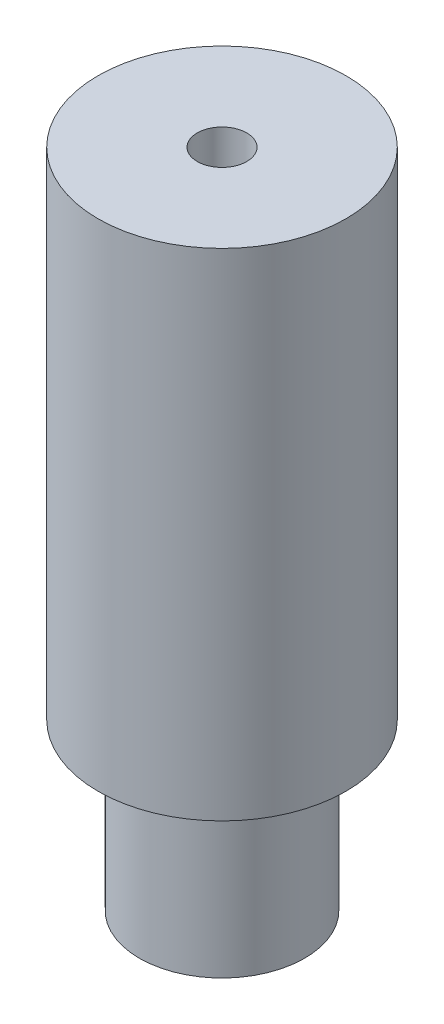
SolidWorks part; units mm, degrees
ref_plane "Front Plane" through (0, 0, 0) normal (0, 0, 1) x (1, 0, 0)
ref_plane "Top Plane" through (0, 0, 0) normal (0, 1, 0) x (1, 0, 0)
ref_plane "Right Plane" through (0, 0, 0) normal (1, 0, 0) x (0, 0, -1)
sketch "Sketch1" plane through (0, 0, 0) normal (0, 1, 0) x (1, 0, 0)
  circle A0 centre (0, 0) radius 5
  dimension "D1" = 10
extrude "Boss-Extrude1" add sketch "Sketch1" along normal blind 10
sketch "Sketch2" plane through (0, 10, 0) normal (0, 1, 0) x (1, 0, 0)
  circle A0 centre (0, 0) radius 7.5
  dimension "D1" = 15
extrude "Boss-Extrude2" add sketch "Sketch2" along normal blind 30
sketch "Sketch4" plane through (0, 0, 0) normal (0, -1, 0) x (1, 0, 0)
  circle A0 centre (0, 0) radius 3
  dimension "D1" = 6
extrude "Cut-Extrude1" cut sketch "Sketch4" against normal blind 20
sketch "Sketch5" plane through (0, 40, 0) normal (0, 1, 0) x (1, 0, 0)
  circle A0 centre (0, 0) radius 1.5
  dimension "D1" = 3
extrude "Cut-Extrude2" cut sketch "Sketch5" against normal blind 20
